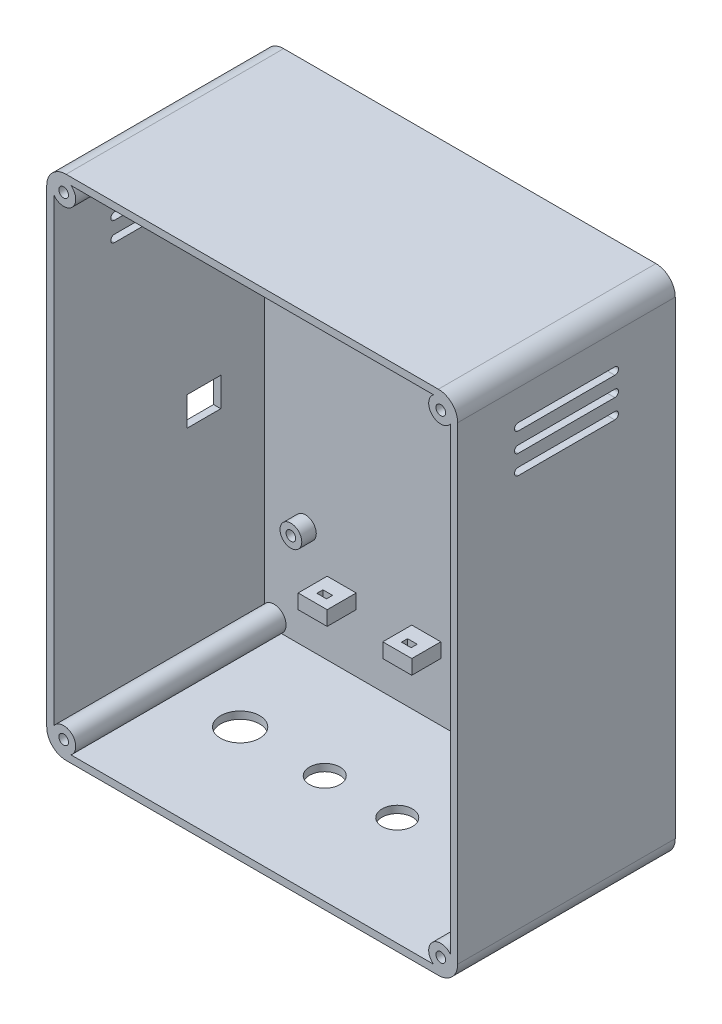
SolidWorks part; units mm, degrees
ref_plane "Front Plane" through (0, 0, 0) normal (0, 0, 1) x (1, 0, 0)
ref_plane "Top Plane" through (0, 0, 0) normal (0, 1, 0) x (1, 0, 0)
ref_plane "Right Plane" through (0, 0, 0) normal (1, 0, 0) x (0, 0, -1)
sketch "Sketch1" plane through (0, 0, 0) normal (0, 0, 1) x (1, 0, 0)
  line L0 (-77, 0) -> (77, 0)
  line L1 (85, 8) -> (85, 202)
  line L2 (77, 210) -> (-77, 210)
  line L3 (-85, 202) -> (-85, 8)
  arc A0 (-85, 8) -> (-77, 0) centre (-77, 8) ccw
  arc A1 (77, 0) -> (85, 8) centre (77, 8) ccw
  arc A2 (85, 202) -> (77, 210) centre (77, 202) ccw
  arc A3 (-77, 210) -> (-85, 202) centre (-77, 202) ccw
extrude "Block" add sketch "Sketch1" along normal blind 90
shell "Shell1" thickness 3
sketch "Sketch2" plane through (0, 0, 0) normal (0, 0, 1) x (1, 0, 0)
  circle A0 centre (-78, 7) radius 5
  circle A1 centre (78, 7) radius 5
  circle A2 centre (-78, 203) radius 5
  circle A3 centre (78, 203) radius 5
extrude "Corner columns" add sketch "Sketch2" along normal blind 90
ref_plane "P1_Front_90" through (0, 0, 90) normal (0, 0, 1) x (1, 0, 0)
sketch "Sketch3" plane through (0, 0, 90) normal (0, 0, 1) x (1, 0, 0)
  circle A0 centre (-78, 7) radius 2
  circle A1 centre (78, 7) radius 2
  circle A2 centre (-78, 203) radius 2
  circle A3 centre (78, 203) radius 2
extrude "Front panel insert holes" cut sketch "Sketch3" against normal blind 7
ref_plane "P2_Front_3" through (0, 0, 3) normal (0, 0, 1) x (1, 0, 0)
sketch "Sketch4" plane through (0, 0, 3) normal (0, 0, 1) x (1, 0, 0)
  circle A0 centre (-65, 46) radius 4.5
  circle A1 centre (65, 46) radius 4.5
  circle A2 centre (-65, 190) radius 4.5
  circle A3 centre (65, 190) radius 4.5
extrude "Plate bosses" add sketch "Sketch4" along normal blind 6
ref_plane "P3_Front_9" through (0, 0, 9) normal (0, 0, 1) x (1, 0, 0)
sketch "Sketch5" plane through (0, 0, 9) normal (0, 0, 1) x (1, 0, 0)
  circle A0 centre (-65, 46) radius 2
  circle A1 centre (65, 46) radius 2
  circle A2 centre (-65, 190) radius 2
  circle A3 centre (65, 190) radius 2
extrude "Plate insert holes" cut sketch "Sketch5" against normal blind 7
sketch "Sketch6" plane through (0, 0, 0) normal (0, 1, 0) x (1, 0, 0)
  circle A0 centre (-50, -45) radius 8.1
  circle A1 centre (-15, -45) radius 6.3
  circle A2 centre (15, -45) radius 6.3
  circle A3 centre (50, -45) radius 6.3
extrude "Cable gland holes" cut sketch "Sketch6" along normal blind 4
sketch "Sketch7" plane through (0, 0, 3) normal (0, 0, 1) x (1, 0, 0)
  line L1 (-56, 27) -> (-44, 27)
  line L2 (-56, 27) -> (-56, 33)
  line L3 (-56, 33) -> (-44, 33)
  line L4 (-44, 27) -> (-44, 33)
  line L5 (-56, 27) -> (-44, 33) construction
  line L6 (-56, 33) -> (-44, 27) construction
  line L7 (-21, 27) -> (-9, 27)
  line L8 (-21, 27) -> (-21, 33)
  line L9 (-21, 33) -> (-9, 33)
  line L10 (-9, 27) -> (-9, 33)
  line L11 (-21, 27) -> (-9, 33) construction
  line L12 (-21, 33) -> (-9, 27) construction
  line L13 (9, 27) -> (21, 27)
  line L14 (9, 27) -> (9, 33)
  line L15 (9, 33) -> (21, 33)
  line L16 (21, 27) -> (21, 33)
  line L17 (9, 27) -> (21, 33) construction
  line L18 (9, 33) -> (21, 27) construction
  line L19 (44, 27) -> (56, 27)
  line L20 (44, 27) -> (44, 33)
  line L21 (44, 33) -> (56, 33)
  line L22 (56, 27) -> (56, 33)
  line L23 (44, 27) -> (56, 33) construction
  line L24 (44, 33) -> (56, 27) construction
  point P0 (-50, 30)
  point P5 (-15, 30)
  point P10 (15, 30)
  point P15 (50, 30)
extrude "Cable tie bars" add sketch "Sketch7" along normal blind 12
ref_plane "P4_Top_26.99" through (0, 26.99, 0) normal (0, 1, 0) x (1, 0, 0)
sketch "Sketch8" plane through (0, 26.99, 0) normal (0, 1, 0) x (1, 0, 0)
  line L1 (-52, -11.25) -> (-48, -11.25)
  line L2 (-52, -11.25) -> (-52, -8.75)
  line L3 (-52, -8.75) -> (-48, -8.75)
  line L4 (-48, -11.25) -> (-48, -8.75)
  line L5 (-52, -11.25) -> (-48, -8.75) construction
  line L6 (-52, -8.75) -> (-48, -11.25) construction
  line L7 (-17, -11.25) -> (-13, -11.25)
  line L8 (-17, -11.25) -> (-17, -8.75)
  line L9 (-17, -8.75) -> (-13, -8.75)
  line L10 (-13, -11.25) -> (-13, -8.75)
  line L11 (-17, -11.25) -> (-13, -8.75) construction
  line L12 (-17, -8.75) -> (-13, -11.25) construction
  line L13 (13, -11.25) -> (17, -11.25)
  line L14 (13, -11.25) -> (13, -8.75)
  line L15 (13, -8.75) -> (17, -8.75)
  line L16 (17, -11.25) -> (17, -8.75)
  line L17 (13, -11.25) -> (17, -8.75) construction
  line L18 (13, -8.75) -> (17, -11.25) construction
  line L19 (48, -11.25) -> (52, -11.25)
  line L20 (48, -11.25) -> (48, -8.75)
  line L21 (48, -8.75) -> (52, -8.75)
  line L22 (52, -11.25) -> (52, -8.75)
  line L23 (48, -11.25) -> (52, -8.75) construction
  line L24 (48, -8.75) -> (52, -11.25) construction
  point P0 (-50, -10)
  point P5 (-15, -10)
  point P10 (15, -10)
  point P15 (50, -10)
extrude "Cable tie slots" cut sketch "Sketch8" along normal blind 6.02
ref_plane "P5_Right_-85" through (-85, 0, 0) normal (1, 0, 0) x (0, 0, -1)
sketch "Sketch9" plane through (-85, 0, 0) normal (1, 0, 0) x (0, 0, -1)
  line L1 (-35, 89) -> (-21, 89)
  line L2 (-35, 89) -> (-35, 101)
  line L3 (-35, 101) -> (-21, 101)
  line L4 (-21, 89) -> (-21, 101)
  line L5 (-35, 89) -> (-21, 101) construction
  line L6 (-35, 101) -> (-21, 89) construction
  point P0 (-28, 95)
extrude "USB access" cut sketch "Sketch9" along normal blind 4
ref_plane "P6_Right_-85" through (-85, 0, 0) normal (1, 0, 0) x (0, 0, -1)
sketch "Sketch10" plane through (-85, 0, 0) normal (1, 0, 0) x (0, 0, -1)
  line L0 (-25, 172) -> (-65, 172) construction
  line L1 (-25, 170.5) -> (-65, 170.5)
  line L2 (-25, 173.5) -> (-65, 173.5)
  line L3 (-25, 180) -> (-65, 180) construction
  line L4 (-25, 178.5) -> (-65, 178.5)
  line L5 (-25, 181.5) -> (-65, 181.5)
  line L6 (-25, 188) -> (-65, 188) construction
  line L7 (-25, 186.5) -> (-65, 186.5)
  line L8 (-25, 189.5) -> (-65, 189.5)
  arc A0 (-25, 170.5) -> (-25, 173.5) centre (-25, 172) ccw
  arc A1 (-65, 173.5) -> (-65, 170.5) centre (-65, 172) ccw
  arc A2 (-25, 178.5) -> (-25, 181.5) centre (-25, 180) ccw
  arc A3 (-65, 181.5) -> (-65, 178.5) centre (-65, 180) ccw
  arc A4 (-25, 186.5) -> (-25, 189.5) centre (-25, 188) ccw
  arc A5 (-65, 189.5) -> (-65, 186.5) centre (-65, 188) ccw
  point P2 (-45, 172)
  point P7 (-45, 180)
  point P14 (-45, 188)
extrude "Vents left" cut sketch "Sketch10" along normal blind 4
ref_plane "P7_Right_85" through (85, 0, 0) normal (1, 0, 0) x (0, 0, -1)
sketch "Sketch11" plane through (85, 0, 0) normal (1, 0, 0) x (0, 0, -1)
  line L0 (-25, 172) -> (-65, 172) construction
  line L1 (-25, 170.5) -> (-65, 170.5)
  line L2 (-25, 173.5) -> (-65, 173.5)
  line L3 (-25, 180) -> (-65, 180) construction
  line L4 (-25, 178.5) -> (-65, 178.5)
  line L5 (-25, 181.5) -> (-65, 181.5)
  line L6 (-25, 188) -> (-65, 188) construction
  line L7 (-25, 186.5) -> (-65, 186.5)
  line L8 (-25, 189.5) -> (-65, 189.5)
  arc A0 (-25, 170.5) -> (-25, 173.5) centre (-25, 172) ccw
  arc A1 (-65, 173.5) -> (-65, 170.5) centre (-65, 172) ccw
  arc A2 (-25, 178.5) -> (-25, 181.5) centre (-25, 180) ccw
  arc A3 (-65, 181.5) -> (-65, 178.5) centre (-65, 180) ccw
  arc A4 (-25, 186.5) -> (-25, 189.5) centre (-25, 188) ccw
  arc A5 (-65, 189.5) -> (-65, 186.5) centre (-65, 188) ccw
  point P2 (-45, 172)
  point P7 (-45, 180)
  point P14 (-45, 188)
extrude "Vents right" cut sketch "Sketch11" against normal blind 4
sketch "Sketch12" plane through (0, 0, 0) normal (0, 0, 1) x (1, 0, 0)
  circle A0 centre (-45, 165) radius 4.75
  circle A1 centre (45, 165) radius 4.75
extrude "Keyhole heads" cut sketch "Sketch12" along normal blind 4
sketch "Sketch13" plane through (0, 0, 0) normal (0, 0, 1) x (1, 0, 0)
  line L0 (-45, 165) -> (-45, 176) construction
  line L1 (-47.4, 165) -> (-47.4, 176)
  line L2 (-42.6, 165) -> (-42.6, 176)
  line L3 (45, 165) -> (45, 176) construction
  line L4 (42.6, 165) -> (42.6, 176)
  line L5 (47.4, 165) -> (47.4, 176)
  arc A0 (-47.4, 165) -> (-42.6, 165) centre (-45, 165) ccw
  arc A1 (-42.6, 176) -> (-47.4, 176) centre (-45, 176) ccw
  arc A2 (42.6, 165) -> (47.4, 165) centre (45, 165) ccw
  arc A3 (47.4, 176) -> (42.6, 176) centre (45, 176) ccw
  point P2 (-45, 170.5)
  point P7 (45, 170.5)
extrude "Keyhole slots" cut sketch "Sketch13" along normal blind 4
